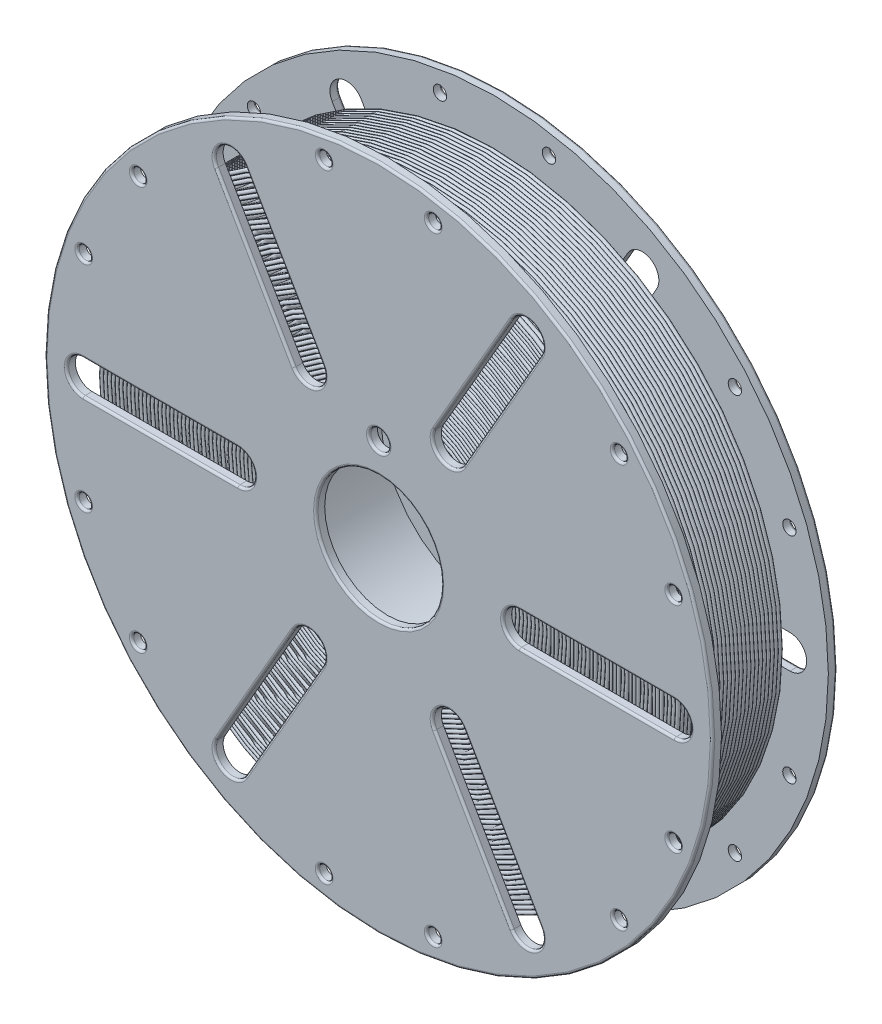
SolidWorks part; units mm, degrees
ref_plane "Front Plane" through (0, 0, 0) normal (0, 0, 1) x (1, 0, 0)
ref_plane "Top Plane" through (0, 0, 0) normal (0, 1, 0) x (1, 0, 0)
ref_plane "Right Plane" through (0, 0, 0) normal (1, 0, 0) x (0, 0, -1)
sketch "Sketch1" plane through (0, 0, 0) normal (0, 0, 1) x (1, 0, 0)
  line L5 (63.25, 0) -> (132.75, 0) construction
  line L6 (63.25, 7.5) -> (132.75, 7.5)
  line L7 (63.25, -7.5) -> (132.75, -7.5)
  line L8 (31.625, -54.7761) -> (66.375, -114.9649) construction
  line L9 (38.1202, -51.0261) -> (72.8702, -111.2149)
  line L10 (25.1298, -58.5261) -> (59.8798, -118.7149)
  line L11 (-31.625, -54.7761) -> (-66.375, -114.9649) construction
  line L12 (-25.1298, -58.5261) -> (-59.8798, -118.7149)
  line L13 (-38.1202, -51.0261) -> (-72.8702, -111.2149)
  line L14 (-63.25, 0) -> (-132.75, 0) construction
  line L15 (-63.25, -7.5) -> (-132.75, -7.5)
  line L16 (-63.25, 7.5) -> (-132.75, 7.5)
  line L17 (-31.625, 54.7761) -> (-66.375, 114.9649) construction
  line L18 (-38.1202, 51.0261) -> (-72.8702, 111.2149)
  line L19 (-25.1298, 58.5261) -> (-59.8798, 118.7149)
  line L20 (31.625, 54.7761) -> (66.375, 114.9649) construction
  line L21 (25.1298, 58.5261) -> (59.8798, 118.7149)
  line L22 (38.1202, 51.0261) -> (72.8702, 111.2149)
  circle A0 centre (0, 0) radius 28.25
  circle A1 centre (0, 0) radius 150
  arc A2 (63.25, 7.5) -> (63.25, -7.5) centre (63.25, 0) ccw
  arc A3 (132.75, -7.5) -> (132.75, 7.5) centre (132.75, 0) ccw
  arc A4 (38.1202, -51.0261) -> (25.1298, -58.5261) centre (31.625, -54.7761) ccw
  arc A5 (59.8798, -118.7149) -> (72.8702, -111.2149) centre (66.375, -114.9649) ccw
  arc A6 (-25.1298, -58.5261) -> (-38.1202, -51.0261) centre (-31.625, -54.7761) ccw
  arc A7 (-72.8702, -111.2149) -> (-59.8798, -118.7149) centre (-66.375, -114.9649) ccw
  arc A8 (-63.25, -7.5) -> (-63.25, 7.5) centre (-63.25, 0) ccw
  arc A9 (-132.75, 7.5) -> (-132.75, -7.5) centre (-132.75, 0) ccw
  arc A10 (-38.1202, 51.0261) -> (-25.1298, 58.5261) centre (-31.625, 54.7761) ccw
  arc A11 (-59.8798, 118.7149) -> (-72.8702, 111.2149) centre (-66.375, 114.9649) ccw
  arc A12 (25.1298, 58.5261) -> (38.1202, 51.0261) centre (31.625, 54.7761) ccw
  arc A13 (72.8702, 111.2149) -> (59.8798, 118.7149) centre (66.375, 114.9649) ccw
  circle A14 centre (141, 0) radius 3 construction
  circle A15 centre (132.4967, -48.2248) radius 3
  circle A16 centre (108.0123, -90.6331) radius 3
  circle A17 centre (70.5, -122.1096) radius 3 construction
  circle A18 centre (24.4844, -138.8579) radius 3
  circle A19 centre (-24.4844, -138.8579) radius 3
  circle A20 centre (-70.5, -122.1096) radius 3 construction
  circle A21 centre (-108.0123, -90.6331) radius 3
  circle A22 centre (-132.4967, -48.2248) radius 3
  circle A23 centre (-141, 0) radius 3 construction
  circle A24 centre (-132.4967, 48.2248) radius 3
  circle A25 centre (-108.0123, 90.6331) radius 3
  circle A26 centre (-70.5, 122.1096) radius 3 construction
  circle A27 centre (-24.4844, 138.8579) radius 3
  circle A28 centre (24.4844, 138.8579) radius 3
  circle A29 centre (70.5, 122.1096) radius 3 construction
  circle A30 centre (108.0123, 90.6331) radius 3
  circle A31 centre (132.4967, 48.2248) radius 3
  circle A32 centre (0, 41.75) radius 4.5
  point P13 (98, 0)
  point P22 (49, -84.8705)
  point P29 (-49, -84.8705)
  point P36 (-98, 0)
  point P43 (-49, 84.8705)
  point P50 (49, 84.8705)
  point P55 (0, 0)
  point P85 (0, 0)
  dimension "D1" = 6
  dimension "D2" = 18
extrude "Boss-Extrude1" add sketch "Sketch1" along normal blind 4
fillet "Fillet1" radius 1 39 edges at (4.5, 41.75, 0) (135.4967, 48.2248, 0) (111.0123, 90.6331, 0) (27.4844, 138.8579, 0) (-21.4844, 138.8579, 0) (-105.0123, 90.6331, 0) (-129.4967, 48.2248, 0) (-129.4967, -48.2248, 0) (-105.0123, -90.6331, 0) (-21.4844, -138.8579, 0) (27.4844, -138.8579, 0) (42.5048, 88.6205, 0) (70.125, 121.4601, 0) (55.4952, 81.1205, 0) (27.875, 48.2809, 0) (-98, -7.5, 0) (-140.25, 0, 0) (-98, 7.5, 0) (-55.75, 0, 0) (55.4952, -81.1205, 0) (70.125, -121.4601, 0) (42.5048, -88.6205, 0) (27.875, -48.2809, 0) (135.4967, -48.2248, 0) (28.25, 0, 0) (150, 0, 0) (98, 7.5, 0) (140.25, 0, 0) (98, -7.5, 0) (55.75, 0, 0) (111.0123, -90.6331, 0) (-42.5048, -88.6205, 0) (-70.125, -121.4601, 0) (-55.4952, -81.1205, 0) (-27.875, -48.2809, 0) (-55.4952, 81.1205, 0) (-70.125, 121.4601, 0) (-42.5048, 88.6205, 0) (-27.875, 48.2809, 0)
ref_plane "Plane1" through (0, 0, 28) normal (0, 0, 1) x (1, 0, 0)
mirror "Mirror2" about plane through (0, 0, 28) normal (0, 0, 1) of bodies 101
sketch "Sketch2" plane through (0, 0, 28) normal (0, 0, 1) x (1, 0, 0)
  circle A0 centre (0, 0) radius 55
extrude "Extrude-Thin1" add sketch "Sketch2" along normal up to vertex and the other way up to vertex thin
sketch "Sketch3" plane through (0, 0, 0) normal (1, 0, 0) x (0, 0, -1)
  line L0 (-52, -55) -> (-52, 55) construction
  line L1 (-52, -55) -> (-52, 55) construction
  line L2 (-28.9129, 129.375) -> (-27.1629, 129.375) construction
  line L3 (-50.7879, 55) -> (-5.2879, 55)
  line L4 (-4, 55) -> (-4, -55) construction
  line L5 (-4, 55) -> (-4, -55) construction
  line L6 (-52, 55) -> (-4, 55) construction
  line L7 (0, 0) -> (-52, 0) construction
  arc A0 (-27.1629, 129.375) -> (-28.9129, 129.375) centre (-28.0379, 129.375) ccw
  arc A1 (-25.4129, 129.375) -> (-27.1629, 129.375) centre (-26.2879, 129.375) ccw
  arc A2 (-23.6629, 129.375) -> (-25.4129, 129.375) centre (-24.5379, 129.375) ccw
  arc A3 (-21.9129, 129.375) -> (-23.6629, 129.375) centre (-22.7879, 129.375) ccw
  arc A4 (-20.1629, 129.375) -> (-21.9129, 129.375) centre (-21.0379, 129.375) ccw
  arc A5 (-18.4129, 129.375) -> (-20.1629, 129.375) centre (-19.2879, 129.375) ccw
  arc A6 (-16.6629, 129.375) -> (-18.4129, 129.375) centre (-17.5379, 129.375) ccw
  arc A7 (-14.9129, 129.375) -> (-16.6629, 129.375) centre (-15.7879, 129.375) ccw
  arc A8 (-13.1629, 129.375) -> (-14.9129, 129.375) centre (-14.0379, 129.375) ccw
  arc A9 (-11.4129, 129.375) -> (-13.1629, 129.375) centre (-12.2879, 129.375) ccw
  arc A10 (-9.6629, 129.375) -> (-11.4129, 129.375) centre (-10.5379, 129.375) ccw
  arc A11 (-7.9129, 129.375) -> (-9.6629, 129.375) centre (-8.7879, 129.375) ccw
  arc A12 (-6.1629, 129.375) -> (-7.9129, 129.375) centre (-7.0379, 129.375) ccw
  arc A14 (-50.7879, 128.5) -> (-49.9129, 129.375) centre (-50.7879, 129.375) cw
  arc A15 (-49.9129, 129.375) -> (-48.1629, 129.375) centre (-49.0379, 129.375) cw
  arc A16 (-48.1629, 129.375) -> (-46.4129, 129.375) centre (-47.2879, 129.375) cw
  arc A17 (-46.4129, 129.375) -> (-44.6629, 129.375) centre (-45.5379, 129.375) cw
  arc A18 (-44.6629, 129.375) -> (-42.9129, 129.375) centre (-43.7879, 129.375) cw
  arc A19 (-42.9129, 129.375) -> (-41.1629, 129.375) centre (-42.0379, 129.375) cw
  arc A20 (-41.1629, 129.375) -> (-39.4129, 129.375) centre (-40.2879, 129.375) cw
  arc A21 (-39.4129, 129.375) -> (-37.6629, 129.375) centre (-38.5379, 129.375) cw
  arc A22 (-37.6629, 129.375) -> (-35.9129, 129.375) centre (-36.7879, 129.375) cw
  arc A23 (-35.9129, 129.375) -> (-34.1629, 129.375) centre (-35.0379, 129.375) cw
  arc A24 (-34.1629, 129.375) -> (-32.4129, 129.375) centre (-33.2879, 129.375) cw
  arc A25 (-32.4129, 129.375) -> (-30.6629, 129.375) centre (-31.5379, 129.375) cw
  arc A26 (-30.6629, 129.375) -> (-28.9129, 129.375) centre (-29.7879, 129.375) cw
  arc A27 (-50.7879, 126.75) -> (-50.7879, 128.5) centre (-50.7879, 127.625) cw
  arc A28 (-50.7879, 125) -> (-50.7879, 126.75) centre (-50.7879, 125.875) cw
  arc A29 (-50.7879, 123.25) -> (-50.7879, 125) centre (-50.7879, 124.125) cw
  arc A30 (-50.7879, 121.5) -> (-50.7879, 123.25) centre (-50.7879, 122.375) cw
  arc A31 (-50.7879, 119.75) -> (-50.7879, 121.5) centre (-50.7879, 120.625) cw
  arc A32 (-50.7879, 118) -> (-50.7879, 119.75) centre (-50.7879, 118.875) cw
  arc A33 (-50.7879, 116.25) -> (-50.7879, 118) centre (-50.7879, 117.125) cw
  arc A34 (-50.7879, 114.5) -> (-50.7879, 116.25) centre (-50.7879, 115.375) cw
  arc A35 (-50.7879, 112.75) -> (-50.7879, 114.5) centre (-50.7879, 113.625) cw
  arc A36 (-50.7879, 111) -> (-50.7879, 112.75) centre (-50.7879, 111.875) cw
  arc A37 (-50.7879, 109.25) -> (-50.7879, 111) centre (-50.7879, 110.125) cw
  arc A38 (-50.7879, 107.5) -> (-50.7879, 109.25) centre (-50.7879, 108.375) cw
  arc A39 (-50.7879, 105.75) -> (-50.7879, 107.5) centre (-50.7879, 106.625) cw
  arc A40 (-50.7879, 104) -> (-50.7879, 105.75) centre (-50.7879, 104.875) cw
  arc A41 (-50.7879, 102.25) -> (-50.7879, 104) centre (-50.7879, 103.125) cw
  arc A42 (-50.7879, 100.5) -> (-50.7879, 102.25) centre (-50.7879, 101.375) cw
  arc A43 (-50.7879, 98.75) -> (-50.7879, 100.5) centre (-50.7879, 99.625) cw
  arc A44 (-50.7879, 97) -> (-50.7879, 98.75) centre (-50.7879, 97.875) cw
  arc A45 (-50.7879, 95.25) -> (-50.7879, 97) centre (-50.7879, 96.125) cw
  arc A46 (-50.7879, 93.5) -> (-50.7879, 95.25) centre (-50.7879, 94.375) cw
  arc A47 (-50.7879, 91.75) -> (-50.7879, 93.5) centre (-50.7879, 92.625) cw
  arc A48 (-50.7879, 90) -> (-50.7879, 91.75) centre (-50.7879, 90.875) cw
  arc A49 (-50.7879, 88.25) -> (-50.7879, 90) centre (-50.7879, 89.125) cw
  arc A50 (-50.7879, 86.5) -> (-50.7879, 88.25) centre (-50.7879, 87.375) cw
  arc A51 (-50.7879, 84.75) -> (-50.7879, 86.5) centre (-50.7879, 85.625) cw
  arc A52 (-50.7879, 83) -> (-50.7879, 84.75) centre (-50.7879, 83.875) cw
  arc A53 (-50.7879, 81.25) -> (-50.7879, 83) centre (-50.7879, 82.125) cw
  arc A54 (-50.7879, 79.5) -> (-50.7879, 81.25) centre (-50.7879, 80.375) cw
  arc A55 (-50.7879, 77.75) -> (-50.7879, 79.5) centre (-50.7879, 78.625) cw
  arc A56 (-50.7879, 76) -> (-50.7879, 77.75) centre (-50.7879, 76.875) cw
  arc A57 (-50.7879, 74.25) -> (-50.7879, 76) centre (-50.7879, 75.125) cw
  arc A58 (-50.7879, 72.5) -> (-50.7879, 74.25) centre (-50.7879, 73.375) cw
  arc A59 (-50.7879, 70.75) -> (-50.7879, 72.5) centre (-50.7879, 71.625) cw
  arc A60 (-50.7879, 69) -> (-50.7879, 70.75) centre (-50.7879, 69.875) cw
  arc A61 (-50.7879, 67.25) -> (-50.7879, 69) centre (-50.7879, 68.125) cw
  arc A62 (-50.7879, 65.5) -> (-50.7879, 67.25) centre (-50.7879, 66.375) cw
  arc A63 (-50.7879, 63.75) -> (-50.7879, 65.5) centre (-50.7879, 64.625) cw
  arc A64 (-50.7879, 62) -> (-50.7879, 63.75) centre (-50.7879, 62.875) cw
  arc A65 (-50.7879, 60.25) -> (-50.7879, 62) centre (-50.7879, 61.125) cw
  arc A66 (-50.7879, 58.5) -> (-50.7879, 60.25) centre (-50.7879, 59.375) cw
  arc A67 (-50.7879, 56.75) -> (-50.7879, 58.5) centre (-50.7879, 57.625) cw
  arc A68 (-50.7879, 55) -> (-50.7879, 56.75) centre (-50.7879, 55.875) cw
  arc A69 (-5.2879, 128.5) -> (-6.1629, 129.375) centre (-5.2879, 129.375) ccw
  arc A70 (-5.2879, 126.75) -> (-5.2879, 128.5) centre (-5.2879, 127.625) ccw
  arc A71 (-5.2879, 55) -> (-5.2879, 56.75) centre (-5.2879, 55.875) ccw
  arc A72 (-5.2879, 56.75) -> (-5.2879, 58.5) centre (-5.2879, 57.625) ccw
  arc A73 (-5.2879, 58.5) -> (-5.2879, 60.25) centre (-5.2879, 59.375) ccw
  arc A74 (-5.2879, 60.25) -> (-5.2879, 62) centre (-5.2879, 61.125) ccw
  arc A75 (-5.2879, 62) -> (-5.2879, 63.75) centre (-5.2879, 62.875) ccw
  arc A76 (-5.2879, 63.75) -> (-5.2879, 65.5) centre (-5.2879, 64.625) ccw
  arc A77 (-5.2879, 65.5) -> (-5.2879, 67.25) centre (-5.2879, 66.375) ccw
  arc A78 (-5.2879, 67.25) -> (-5.2879, 69) centre (-5.2879, 68.125) ccw
  arc A79 (-5.2879, 69) -> (-5.2879, 70.75) centre (-5.2879, 69.875) ccw
  arc A80 (-5.2879, 70.75) -> (-5.2879, 72.5) centre (-5.2879, 71.625) ccw
  arc A81 (-5.2879, 72.5) -> (-5.2879, 74.25) centre (-5.2879, 73.375) ccw
  arc A82 (-5.2879, 74.25) -> (-5.2879, 76) centre (-5.2879, 75.125) ccw
  arc A83 (-5.2879, 76) -> (-5.2879, 77.75) centre (-5.2879, 76.875) ccw
  arc A84 (-5.2879, 77.75) -> (-5.2879, 79.5) centre (-5.2879, 78.625) ccw
  arc A85 (-5.2879, 79.5) -> (-5.2879, 81.25) centre (-5.2879, 80.375) ccw
  arc A86 (-5.2879, 81.25) -> (-5.2879, 83) centre (-5.2879, 82.125) ccw
  arc A87 (-5.2879, 83) -> (-5.2879, 84.75) centre (-5.2879, 83.875) ccw
  arc A88 (-5.2879, 84.75) -> (-5.2879, 86.5) centre (-5.2879, 85.625) ccw
  arc A89 (-5.2879, 86.5) -> (-5.2879, 88.25) centre (-5.2879, 87.375) ccw
  arc A90 (-5.2879, 88.25) -> (-5.2879, 90) centre (-5.2879, 89.125) ccw
  arc A91 (-5.2879, 90) -> (-5.2879, 91.75) centre (-5.2879, 90.875) ccw
  arc A92 (-5.2879, 91.75) -> (-5.2879, 93.5) centre (-5.2879, 92.625) ccw
  arc A93 (-5.2879, 93.5) -> (-5.2879, 95.25) centre (-5.2879, 94.375) ccw
  arc A94 (-5.2879, 95.25) -> (-5.2879, 97) centre (-5.2879, 96.125) ccw
  arc A95 (-5.2879, 97) -> (-5.2879, 98.75) centre (-5.2879, 97.875) ccw
  arc A96 (-5.2879, 98.75) -> (-5.2879, 100.5) centre (-5.2879, 99.625) ccw
  arc A97 (-5.2879, 100.5) -> (-5.2879, 102.25) centre (-5.2879, 101.375) ccw
  arc A98 (-5.2879, 102.25) -> (-5.2879, 104) centre (-5.2879, 103.125) ccw
  arc A99 (-5.2879, 104) -> (-5.2879, 105.75) centre (-5.2879, 104.875) ccw
  arc A100 (-5.2879, 105.75) -> (-5.2879, 107.5) centre (-5.2879, 106.625) ccw
  arc A101 (-5.2879, 107.5) -> (-5.2879, 109.25) centre (-5.2879, 108.375) ccw
  arc A102 (-5.2879, 109.25) -> (-5.2879, 111) centre (-5.2879, 110.125) ccw
  arc A103 (-5.2879, 111) -> (-5.2879, 112.75) centre (-5.2879, 111.875) ccw
  arc A104 (-5.2879, 112.75) -> (-5.2879, 114.5) centre (-5.2879, 113.625) ccw
  arc A105 (-5.2879, 114.5) -> (-5.2879, 116.25) centre (-5.2879, 115.375) ccw
  arc A106 (-5.2879, 116.25) -> (-5.2879, 118) centre (-5.2879, 117.125) ccw
  arc A107 (-5.2879, 118) -> (-5.2879, 119.75) centre (-5.2879, 118.875) ccw
  arc A108 (-5.2879, 119.75) -> (-5.2879, 121.5) centre (-5.2879, 120.625) ccw
  arc A109 (-5.2879, 121.5) -> (-5.2879, 123.25) centre (-5.2879, 122.375) ccw
  arc A110 (-5.2879, 123.25) -> (-5.2879, 125) centre (-5.2879, 124.125) ccw
  arc A111 (-5.2879, 125) -> (-5.2879, 126.75) centre (-5.2879, 125.875) ccw
  arc A112 (-4.4129, 129.375) -> (-6.1629, 129.375) centre (-5.2879, 129.375) ccw [skipped]
  dimension "D1" = 14
  dimension "D2" = 43
revolve "Revolve1" add sketch "Sketch3" angle 360 about L7
